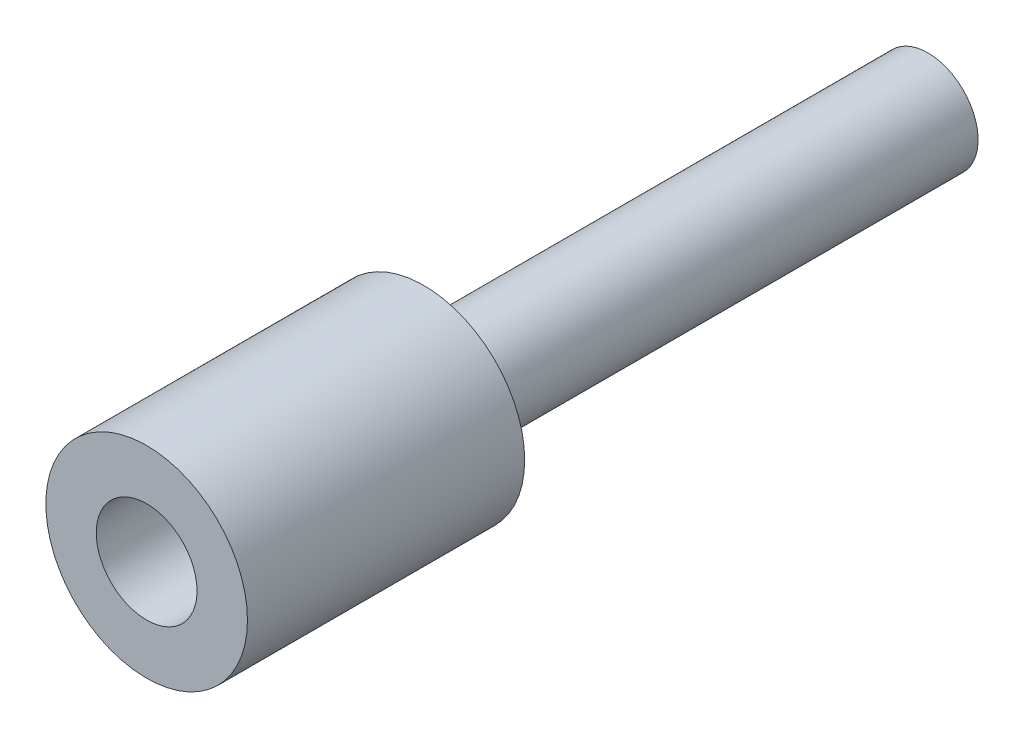
SolidWorks part; units mm, degrees
ref_plane "Front Plane" through (0, 0, 0) normal (0, 0, 1) x (1, 0, 0)
ref_plane "Top Plane" through (0, 0, 0) normal (0, 1, 0) x (1, 0, 0)
ref_plane "Right Plane" through (0, 0, 0) normal (1, 0, 0) x (0, 0, -1)
sketch "Sketch1" plane through (0, 0, 0) normal (0, 0, 1) x (1, 0, 0)
  circle A0 centre (0, 0) radius 4
  circle A1 centre (0, 0) radius 2
  dimension "D1" = 2
  dimension "D2" = 4
extrude "Boss-Extrude1" add sketch "Sketch1" along normal blind 11
sketch "Sketch2" plane through (0, 0, 0) normal (0, 0, -1) x (-1, 0, 0)
  circle A0 centre (0, 0) radius 1.9903
extrude "Boss-Extrude2" add sketch "Sketch2" along normal blind 20 separate body
